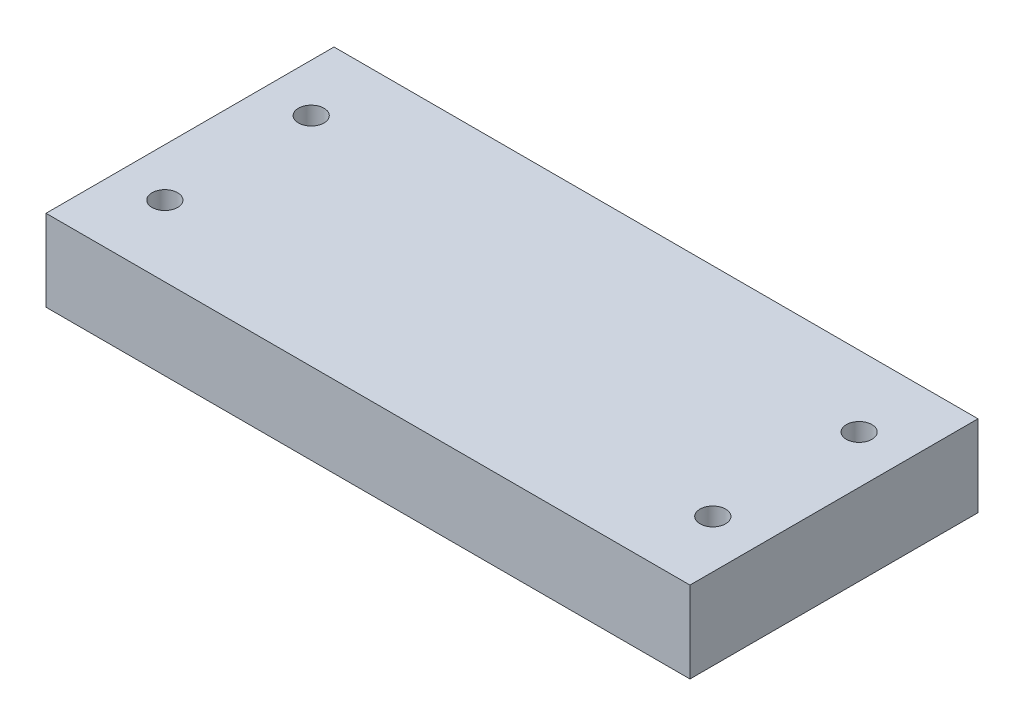
SolidWorks part; units mm, degrees
material "6061-T6 (SS)"
ref_plane "Frontal Plane" through (0, 0, 0) normal (0, 0, 1) x (1, 0, 0)
ref_plane "Horizontal Plane" through (0, 0, 0) normal (0, 1, 0) x (1, 0, 0)
ref_plane "Profile Plane" through (0, 0, 0) normal (1, 0, 0) x (0, 0, -1)
sketch "Sketch1" plane through (0, 0, 0) normal (0, 1, 0) x (1, 0, 0)
  line L1 (-69.85, -31.242) -> (69.85, -31.242)
  line L2 (-69.85, -31.242) -> (-69.85, 31.242)
  line L3 (-69.85, 31.242) -> (69.85, 31.242)
  line L4 (69.85, -31.242) -> (69.85, 31.242)
  line L5 (-69.85, -31.242) -> (69.85, 31.242) construction
  line L6 (-69.85, 31.242) -> (69.85, -31.242) construction
  point P0 (0, 0)
  dimension "D1" = 62.484
  dimension "D2" = 139.7
extrude "Boss-Extrude1" add sketch "Sketch1" along normal blind 17.653
sketch "Sketch2" plane through (0, 17.653, 0) normal (0, 1, 0) x (1, 0, 0)
  circle A0 centre (-59.436, -15.875) radius 2.7781
  dimension "D3" = 5.5562
  dimension "D1" = 15.875
  dimension "D2" = 59.436
extrude "Cut-Extrude1" cut sketch "Sketch2" against normal through all
pattern_linear "LPattern1" count 2 spacing 31.75 along (0, 0, -1) count 2 spacing 118.872 along (1, 0, 0) of "Cut-Extrude1"
sketch "Sketch3" [suppressed] plane through (0, 0, 0) normal (0, 1, 0) x (1, 0, 0)
  line L1 (-98.0585, -4.0715) -> (-72.6585, -4.0715) construction
  line L2 (-98.0585, -4.0715) -> (-98.0585, -29.4715) construction
  line L3 (-98.0585, -29.4715) -> (-72.6585, -29.4715) construction
  line L4 (-72.6585, -4.0715) -> (-72.6585, -29.4715) construction
  line L5 (-98.0585, -4.0715) -> (-72.6585, -29.4715) construction
  line L6 (-98.0585, -29.4715) -> (-72.6585, -4.0715) construction
  point P0 (-85.3585, -16.7715)
  dimension "D1" = 25.4
